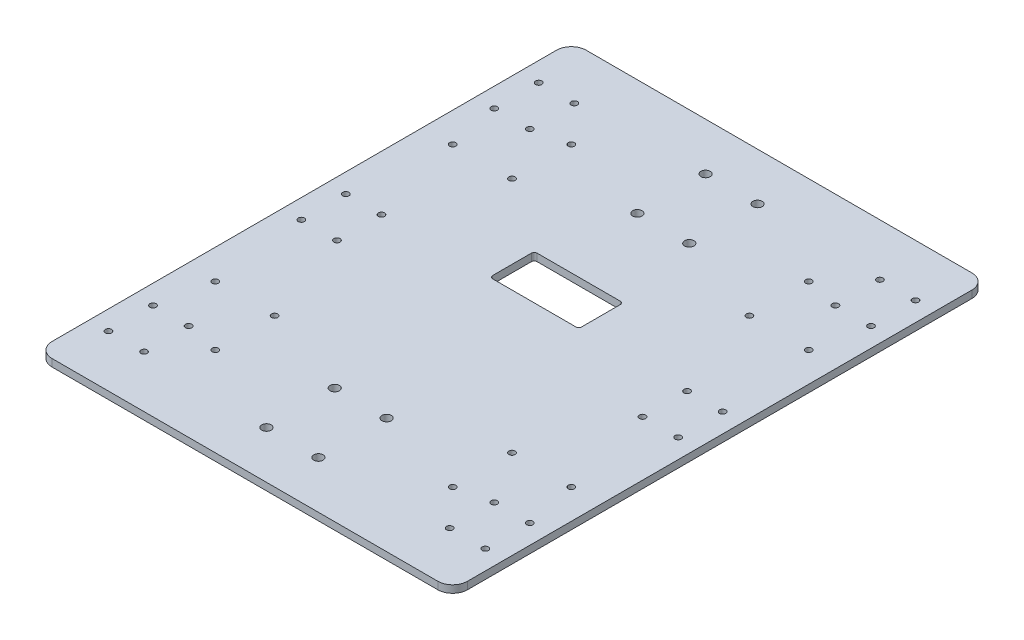
SolidWorks part; units mm, degrees
ref_plane "前视基准面" through (0, 0, 0) normal (0, 0, 1) x (1, 0, 0)
ref_plane "上视基准面" through (0, 0, 0) normal (0, 1, 0) x (1, 0, 0)
ref_plane "右视基准面" through (0, 0, 0) normal (1, 0, 0) x (0, 0, -1)
sketch "草图1" plane through (0, 0, 0) normal (0, 1, 0) x (1, 0, 0)
  line L0 (-827.3485, 0) -> (1282.6464, 0) construction
  line L1 (-180, -180) -> (180, -180)
  line L2 (-180, -180) -> (-180, -160)
  line L3 (-180, 180) -> (180, 180)
  line L4 (180, -180) -> (180, -160)
  line L5 (-180, -180) -> (180, 180) construction
  line L6 (-180, 180) -> (180, -180) construction
  line L7 (0, 735.8923) -> (0, -671.7384) construction
  line L8 (-39.4384, -125) -> (44.3654, -125) construction
  line L9 (-43.0485, 125) -> (27.9521, 125) construction
  line L10 (-119.0715, 130) -> (-237.2387, 130) construction
  line L11 (-115, 130) -> (115, 130) construction
  line L12 (-115, 130) -> (-115, -130) construction
  line L13 (-115, -130) -> (115, -130) construction
  line L14 (115, 130) -> (115, -130) construction
  line L15 (-115, 130) -> (115, -130) construction
  line L16 (-115, -130) -> (115, 130) construction
  line L17 (-180, 160) -> (-180, 180)
  line L18 (-141, 160) -> (-180, 160)
  line L19 (-141, 160) -> (-141, 100)
  line L20 (-141, 100) -> (-180, 100)
  line L21 (141, 100) -> (180, 100)
  line L22 (-141, 160) -> (-180, 100) construction
  line L23 (-141, 100) -> (-180, 160) construction
  line L24 (141, 160) -> (141, 100)
  line L25 (141, 160) -> (180, 160)
  line L26 (180, 160) -> (180, 180)
  line L27 (141, -160) -> (180, -160)
  line L28 (141, -160) -> (141, -100)
  line L29 (141, -100) -> (180, -100)
  line L30 (-141, -100) -> (-180, -100)
  line L31 (-141, -160) -> (-141, -100)
  line L32 (-141, -160) -> (-180, -160)
  line L33 (-180, -100) -> (-180, -30)
  line L34 (180, -100) -> (180, -30)
  line L35 (-180, 30) -> (-141, 30)
  line L36 (-141, 30) -> (-141, -30)
  line L37 (-180, -30) -> (-141, -30)
  line L38 (-180, 30) -> (-180, 100)
  line L39 (180, 30) -> (141, 30)
  line L40 (141, 30) -> (141, -30)
  line L41 (180, -30) -> (141, -30)
  line L42 (180, 30) -> (180, 100)
  circle A0 centre (-103, 145) radius 2.1
  circle A1 centre (-103, 115) radius 2.1
  circle A2 centre (-127, 145) radius 2.1
  circle A3 centre (-127, 115) radius 2.1
  circle A4 centre (103, 145) radius 2.1
  circle A5 centre (103, 115) radius 2.1
  circle A6 centre (127, 145) radius 2.1
  circle A7 centre (127, 115) radius 2.1
  circle A8 centre (127, -115) radius 2.1
  circle A9 centre (127, -145) radius 2.1
  circle A10 centre (103, -145) radius 2.1
  circle A11 centre (103, -115) radius 2.1
  circle A12 centre (-127, -115) radius 2.1
  circle A13 centre (-103, -115) radius 2.1
  circle A14 centre (-103, -145) radius 2.1
  circle A15 centre (-127, -145) radius 2.1
  circle A16 centre (17.5, -102) radius 3.15
  circle A17 centre (-17.5, -102) radius 3.15
  circle A18 centre (-17.5, -148) radius 3.15
  circle A19 centre (17.5, -148) radius 3.15
  circle A20 centre (-17.5, 148) radius 3.15
  circle A21 centre (17.5, 148) radius 3.15
  circle A22 centre (17.5, 102) radius 3.15
  circle A23 centre (-17.5, 102) radius 3.15
  circle A24 centre (-103, 15) radius 2.1
  circle A25 centre (-103, -15) radius 2.1
  circle A26 centre (-127, 15) radius 2.1
  circle A27 centre (-127, -15) radius 2.1
  circle A28 centre (127, 15) radius 2.1
  circle A29 centre (127, -15) radius 2.1
  circle A30 centre (103, 15) radius 2.1
  circle A31 centre (103, -15) radius 2.1
  point P0 (0, 0)
  point P22 (0, 0)
  point P69 (-160.5, 130)
  point P107 (-141, 0)
  dimension "D3" = 4.2
  dimension "D4" = 24
  dimension "D5" = 30
  dimension "D6" = 4.2
  dimension "D7" = 30
  dimension "D8" = 24
  dimension "D9" = 4.2
  dimension "D10" = 30
  dimension "D11" = 24
  dimension "D12" = 4.2
  dimension "D13" = 24
  dimension "D14" = 30
  dimension "D17" = 6.3
  dimension "D18" = 35
  dimension "D19" = 46
  dimension "D21" = 6.3
  dimension "D22" = 35
  dimension "D23" = 46
  dimension "D27" = 4.2
  dimension "D28" = 30
  dimension "D29" = 24
  dimension "D30" = 4.2
  dimension "D31" = 30
  dimension "D32" = 24
  dimension "D1" = 360
  dimension "D2" = 360
  dimension "D15" = 230
  dimension "D16" = 260
  dimension "D20" = 125
  dimension "D24" = 125
  dimension "D25" = 60
  dimension "D26" = 26
  dimension "D33" = 26
  dimension "D34" = 60
extrude "凸台-拉伸1" add sketch "草图1" along normal blind 5
sketch "草图2" plane through (0, 5, 0) normal (0, 1, 0) x (1, 0, 0)
  line L2 (-140, 180) -> (140, 180)
  line L3 (-140, 180) -> (-140, -180)
  line L4 (-140, -180) -> (140, -180)
  line L5 (140, 180) -> (140, -180)
  line L6 (-140, 180) -> (140, -180) construction
  line L9 (-140, -180) -> (140, 180) construction
  point P0 (0, 0)
  point P1 (0, 0)
  dimension "D1" = 280
  dimension "D2" = 360
extrude "切除-拉伸2" cut sketch "草图2" against normal blind 10 flip side to cut
sketch "草图3" plane through (0, 5, 0) normal (0, 1, 0) x (1, 0, 0)
  line L0 (-236.4858, 0) -> (264.9489, 0) construction
  line L1 (0, 257.4322) -> (0, -271.0364) construction
  circle A0 centre (-80, 80) radius 2.1
  circle A1 centre (-120, 80) radius 2.1
  circle A2 centre (-80, 120) radius 2.1
  circle A3 centre (-80, -120) radius 2.1
  circle A4 centre (-120, -80) radius 2.1
  circle A5 centre (-80, -80) radius 2.1
  circle A6 centre (80, -80) radius 2.1
  circle A7 centre (120, -80) radius 2.1
  circle A8 centre (80, -120) radius 2.1
  circle A9 centre (80, 120) radius 2.1
  circle A10 centre (120, 80) radius 2.1
  circle A11 centre (80, 80) radius 2.1
  dimension "D1" = 4.2
  dimension "D2" = 80
  dimension "D3" = 80
  dimension "D4" = 4.2
  dimension "D5" = 80
  dimension "D6" = 120
  dimension "D7" = 4.2
  dimension "D9" = 120
  dimension "D8" = 80
extrude "切除-拉伸3" cut sketch "草图3" against normal through all
sketch "草图5" plane through (0, 0, 0) normal (0, -1, 0) x (1, 0, 0)
  line L0 (0, -82.7398) -> (0, 197.693) construction
  line L1 (-171.4288, -30) -> (201.8797, -30) construction
  line L3 (-28, -45) -> (28, -45)
  line L4 (-30, -43) -> (-30, -17)
  line L5 (-28, -15) -> (28, -15)
  line L6 (30, -43) -> (30, -17)
  line L7 (-30, -45) -> (30, -15) construction
  line L8 (-30, -15) -> (30, -45) construction
  arc A0 (28, -15) -> (30, -17) centre (28, -17) cw
  arc A1 (28, -45) -> (30, -43) centre (28, -43) ccw
  arc A2 (-28, -45) -> (-30, -43) centre (-28, -43) cw
  arc A3 (-30, -17) -> (-28, -15) centre (-28, -17) cw
  point P5 (0, -30)
  dimension "D4" = 2
  dimension "D1" = 60
  dimension "D2" = 30
  dimension "D3" = 30
extrude "切除-拉伸5" cut sketch "草图5" against normal blind 10
fillet "圆角1" radius 10 4 edges at (140, 2.5, 180) (140, 2.5, -180) (-140, 2.5, 180) (-140, 2.5, -180)
